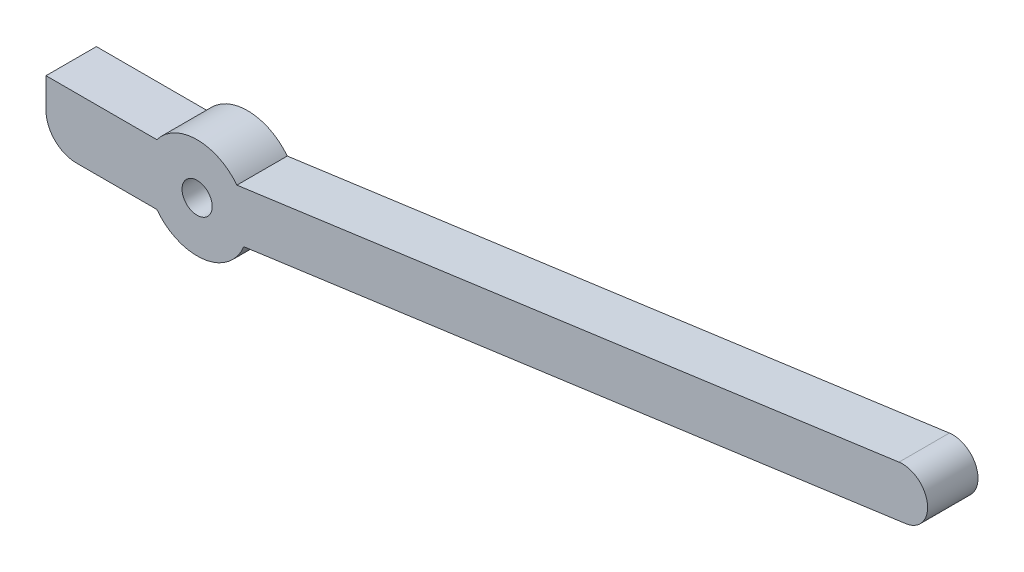
SolidWorks part; units mm, degrees
ref_plane "Front Plane" through (0, 0, 0) normal (0, 0, 1) x (1, 0, 0)
ref_plane "Top Plane" through (0, 0, 0) normal (0, 1, 0) x (1, 0, 0)
ref_plane "Right Plane" through (0, 0, 0) normal (1, 0, 0) x (0, 0, -1)
sketch "Sketch1" plane through (0, 0, 0) normal (0, 0, 1) x (1, 0, 0)
  line L1 (-12.5, -3) -> (-4.5, -3)
  line L3 (-12.5, 3) -> (-4.5, 3)
  line L5 (-12.5, -3) -> (0.9814, 0.2355) construction
  line L6 (-12.5, 3) -> (0.9814, -0.2355) construction
  line L8 (-12.5, 3) -> (-15.5, 3)
  line L10 (-12.5, -3) -> (-15.5, -3)
  line L11 (-15.5, 3) -> (-15.5, -3)
  circle A0 centre (-0.5, 0) radius 1.5
  arc A1 (3.5, 3) -> (-4.5, 3) centre (-0.5, 0) ccw
  arc A2 (-4.5, -3) -> (3.5, -3) centre (-0.5, 0) ccw
  arc A3 (3.5, 3) -> (3.5, -3) centre (-0.5, 0) cw
  point P0 (0, 0)
  dimension "D3" = 3
  dimension "D1" = 6
  dimension "D2" = 3
extrude "Boss-Extrude1" add sketch "Sketch1" along normal blind 5
fillet "Fillet1" radius 3 1 edges at (-15.5, -3, 2.5)
sketch "Sketch2" plane through (0, 0, 5) normal (0, 0, 1) x (1, 0, 0)
  line L1 (4.1306, -1.8861) -> (69.841, 7.1604)
  line L2 (3.4487, 3.0672) -> (69.159, 12.1137)
  arc A0 (69.841, 7.1604) -> (69.159, 12.1137) centre (69.5, 9.637) ccw
  arc A1 (3.4487, 3.0672) -> (4.1306, -1.8861) centre (-0.5, 0) cw
extrude "Boss-Extrude2" add sketch "Sketch2" against normal blind 5
